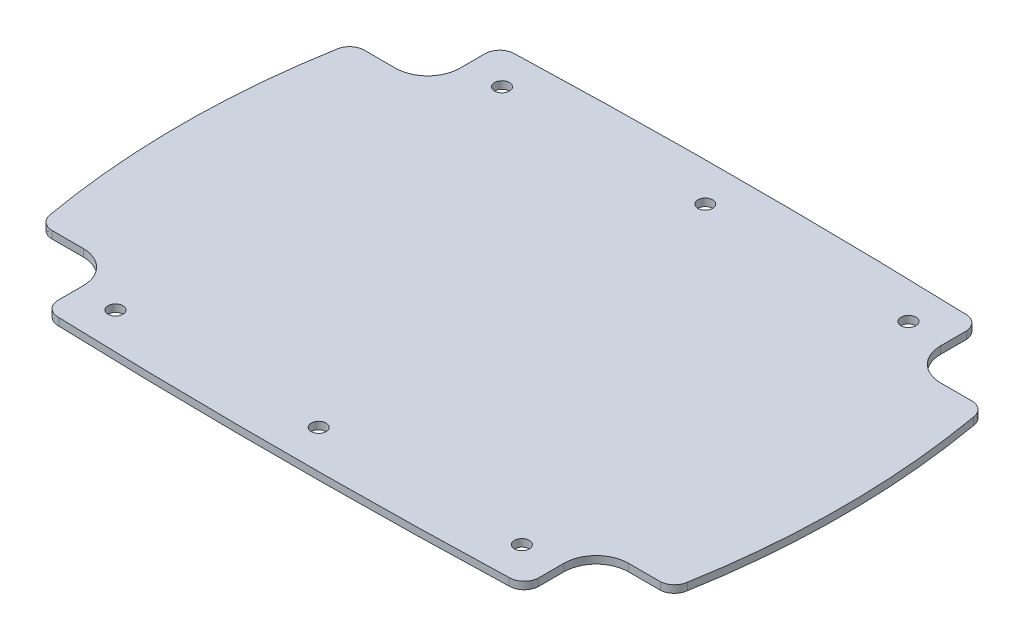
SolidWorks part; units mm, degrees
ref_plane "Спереди" through (0, 0, 0) normal (0, 0, 1) x (1, 0, 0)
ref_plane "Сверху" through (0, 0, 0) normal (0, 1, 0) x (1, 0, 0)
ref_plane "Справа" through (0, 0, 0) normal (1, 0, 0) x (0, 0, -1)
sketch "Эскиз1" plane through (0, 0, 0) normal (0, 1, 0) x (1, 0, 0)
  line L8 (-55.2376, 32.0534) -> (-61.7059, 32.0534)
  line L9 (-55.2376, -30.9466) -> (-61.5144, -30.9466)
  line L10 (-48.7376, -42.6959) -> (-48.7376, -37.4466)
  line L11 (48.2624, -42.6959) -> (48.2624, -37.4466)
  line L12 (54.7624, -30.9466) -> (61.2307, -30.9466)
  line L13 (54.7624, 32.0534) -> (61.2307, 32.0534)
  line L14 (48.2624, 43.8026) -> (48.2624, 38.5534)
  line L15 (-48.7376, 43.8026) -> (-48.7376, 38.5534)
  arc A8 (-64.501, 29.3962) -> (-64.4695, -28.4685) centre (99.7624, 0.5534) ccw
  arc A9 (-48.7376, -37.4466) -> (-55.2376, -30.9466) centre (-55.2376, -37.4466) ccw
  arc A10 (-45.6333, -45.4852) -> (45.1581, -45.4852) centre (-0.2376, 1350.5534) ccw
  arc A11 (54.7624, -30.9466) -> (48.2624, -37.4466) centre (54.7624, -37.4466) ccw
  arc A12 (64.0258, -28.2894) -> (64.0258, 29.3962) centre (-100.2376, 0.5534) ccw
  arc A13 (48.2624, 38.5534) -> (54.7624, 32.0534) centre (54.7624, 38.5534) ccw
  arc A14 (45.1581, 46.592) -> (-45.6333, 46.592) centre (-0.2376, -1349.4466) ccw
  arc A15 (-55.2376, 32.0534) -> (-48.7376, 38.5534) centre (-55.2376, 38.5534) ccw
  circle A16 centre (-41.2376, 39.5534) radius 1.5
  circle A17 centre (-0.2376, 39.5534) radius 1.5
  circle A18 centre (40.7624, 39.5534) radius 1.5
  circle A19 centre (-41.2376, -38.4466) radius 1.5
  circle A20 centre (-0.2376, -38.4466) radius 1.5
  circle A21 centre (40.7624, -38.4466) radius 1.5
  spline S16 degree 3 poles (-61.7059, 32.0534) (-62.0525, 32.0318) (-62.7441, 31.8655) (-63.6291, 31.2777) (-64.2608, 30.4239) (-64.462, 29.7414) (-64.501, 29.3962) knots 0 0 0 0 0.25 0.5 0.75 1 1 1 1
  spline S17 degree 3 poles (-64.4695, -28.4685) (-64.409, -28.8105) (-64.166, -29.4788) (-63.4823, -30.2919) (-62.5629, -30.8235) (-61.8619, -30.9466) (-61.5144, -30.9466) knots 0 0 0 0 0.25 0.5 0.75 1 1 1 1
  spline S18 degree 3 poles (-48.7376, -42.6959) (-48.7109, -43.0772) (-48.5077, -43.8375) (-47.7997, -44.7735) (-46.7959, -45.3774) (-46.0159, -45.4994) (-45.6333, -45.4852) knots 0 0 0 0 0.25 0.5 0.75 1 1 1 1
  spline S19 degree 3 poles (45.1581, -45.4852) (45.5399, -45.4994) (46.3174, -45.3786) (47.3234, -44.7744) (48.0309, -43.8409) (48.2357, -43.078) (48.2624, -42.6959) knots 0 0 0 0 0.25 0.5 0.75 1 1 1 1
  spline S20 degree 3 poles (61.2307, -30.9466) (61.5773, -30.925) (62.2689, -30.7587) (63.1539, -30.1709) (63.7857, -29.3171) (63.9868, -28.6346) (64.0258, -28.2894) knots 0 0 0 0 0.25 0.5 0.75 1 1 1 1
  spline S21 degree 3 poles (64.0258, 29.3962) (63.9868, 29.7412) (63.7859, 30.4234) (63.154, 31.2775) (62.2695, 31.8652) (61.5775, 32.0318) (61.2307, 32.0534) knots 0 0 0 0 0.25 0.5 0.75 1 1 1 1
  spline S22 degree 3 poles (48.2624, 43.8026) (48.2357, 44.1839) (48.0326, 44.9443) (47.3245, 45.8803) (46.3207, 46.4842) (45.5407, 46.6062) (45.1581, 46.592) knots 0 0 0 0 0.25 0.5 0.75 1 1 1 1
  spline S23 degree 3 poles (-45.6333, 46.592) (-46.0151, 46.6062) (-46.7926, 46.4854) (-47.7986, 45.8812) (-48.5061, 44.9477) (-48.7109, 44.1848) (-48.7376, 43.8026) knots 0 0 0 0 0.25 0.5 0.75 1 1 1 1
  point P0 (0, 0)
  dimension "D1" = 3
extrude "Бобышка-Вытянуть1" add sketch "Эскиз1" along normal blind 1.5
